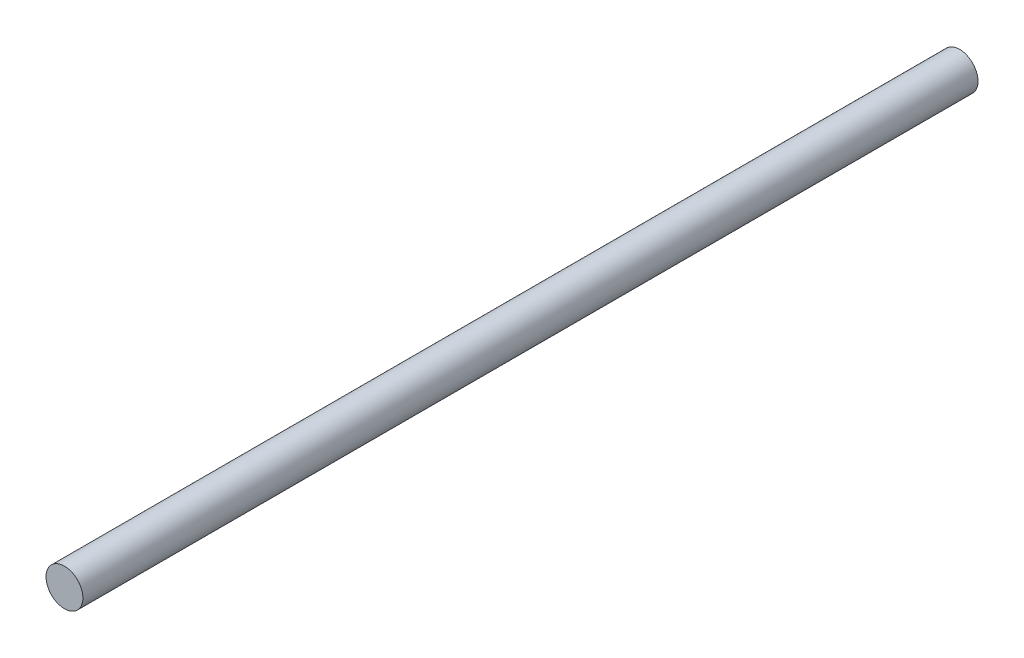
SolidWorks part; units mm, degrees
ref_plane "Front Plane" through (0, 0, 0) normal (0, 0, 1) x (1, 0, 0)
ref_plane "Top Plane" through (0, 0, 0) normal (0, 1, 0) x (1, 0, 0)
ref_plane "Right Plane" through (0, 0, 0) normal (1, 0, 0) x (0, 0, -1)
sketch "Sketch1" plane through (0, 0, 0) normal (0, 0, 1) x (1, 0, 0)
  circle A0 centre (0, 0) radius 4
  dimension "D1" = 8
extrude "Boss-Extrude1" add sketch "Sketch1" along normal blind 194
